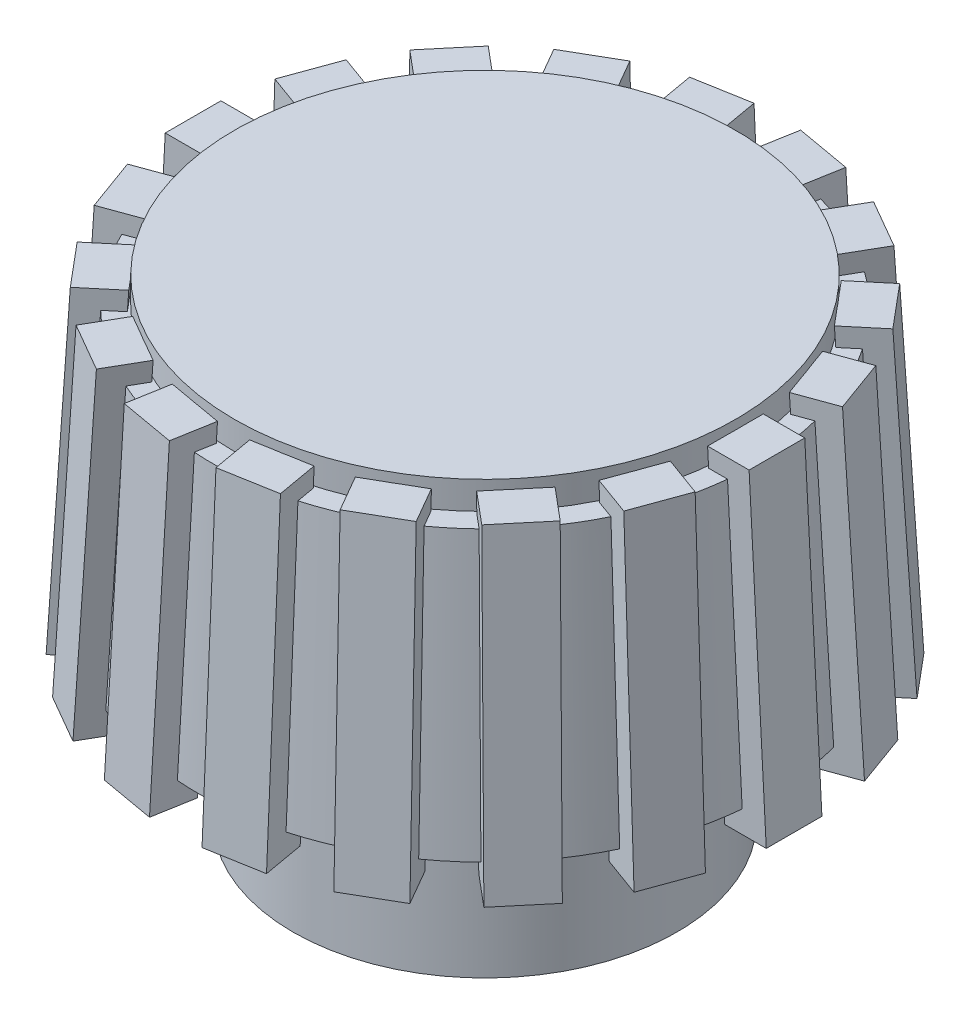
SolidWorks part; units mm, degrees
ref_plane "Front Plane" through (0, 0, 0) normal (0, 0, 1) x (1, 0, 0)
ref_plane "Top Plane" through (0, 0, 0) normal (0, 1, 0) x (1, 0, 0)
ref_plane "Right Plane" through (0, 0, 0) normal (1, 0, 0) x (0, 0, -1)
sketch "Sketch1" plane through (0, 0, 0) normal (0, 1, 0) x (1, 0, 0)
  circle A0 centre (0, 0) radius 3.45
  dimension "D1" = 6.9
extrude "Boss-Extrude1" add sketch "Sketch1" along normal blind 3
sketch "Sketch2" plane through (0, 3, 0) normal (0, 1, 0) x (1, 0, 0)
  circle A0 centre (0, 0) radius 5.1444
extrude "Boss-Extrude2" add sketch "Sketch2" along normal blind 5 draft 3
sketch "Sketch3" plane through (0, 0, 0) normal (0, 0, 1) x (1, 0, 0)
  line L0 (0, 12.8447) -> (0, -3.9119) construction
sketch "Sketch4" plane through (0, 0, 0) normal (0, 0, 1) x (1, 0, 0)
  line L0 (-4.4984, 8.335) -> (-4.8068, 2.6028)
  line L1 (-4.8068, 2.6028) -> (-5.5523, 2.6028)
  line L2 (-5.5523, 2.6028) -> (-5.2438, 8.335)
  line L3 (-5.2438, 8.335) -> (-4.4984, 8.335)
extrude "Boss-Extrude3" add sketch "Sketch4" along normal mid plane 1
pattern_circular "CirPattern1" count 18 over 360 about axis through (0, 0, 0) along (0, 1, 0) of "Boss-Extrude3"
sketch "Sketch5" plane through (0, 8, 0) normal (0, 1, 0) x (1, 0, 0)
  line L0 (4.3981, -1.0687) -> (4.0561, -2.0084) construction
  circle A0 centre (0, 0) radius 4.5
  dimension "D1" = 9
  dimension "D2" = 4.4984
extrude "Boss-Extrude5" add sketch "Sketch5" along normal blind 0.5
